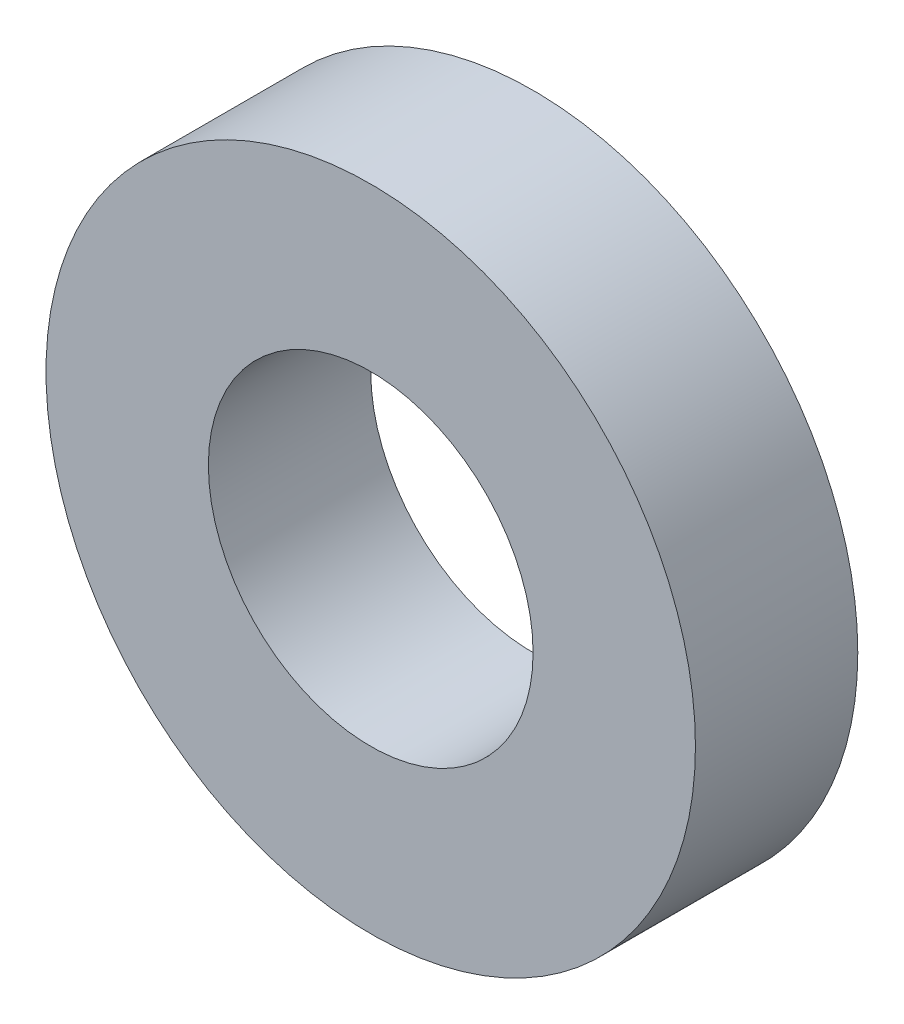
SolidWorks part; units mm, degrees
material "Alloy Steel"
ref_plane "Front" through (0, 0, 0) normal (0, 0, 1) x (1, 0, 0)
ref_plane "Top" through (0, 0, 0) normal (0, 1, 0) x (1, 0, 0)
ref_plane "Right" through (0, 0, 0) normal (1, 0, 0) x (0, 0, -1)
sketch "Sketch1" plane through (0, 0, 0) normal (0, 0, 1) x (1, 0, 0)
  circle A0 centre (0, 0) radius 25.4
  circle A1 centre (0, 0) radius 12.7
  dimension "D1" = 50.8
  dimension "D2" = 25.4
extrude "Boss-Extrude1" add sketch "Sketch1" along normal blind 12.7
